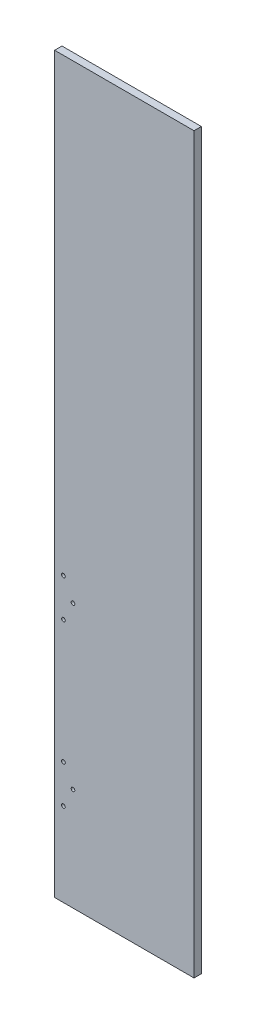
SolidWorks part; units mm, degrees
ref_plane "Front Plane" through (0, 0, 0) normal (0, 0, 1) x (1, 0, 0)
ref_plane "Top Plane" through (0, 0, 0) normal (0, 1, 0) x (1, 0, 0)
ref_plane "Right Plane" through (0, 0, 0) normal (1, 0, 0) x (0, 0, -1)
sketch "Sketch1" plane through (0, 0, 0) normal (0, 0, 1) x (1, 0, 0)
  line L1 (95, -500) -> (-95, -500)
  line L2 (95, -500) -> (95, 500)
  line L3 (95, 500) -> (-95, 500)
  line L4 (-95, -500) -> (-95, 500)
  line L5 (95, -500) -> (-95, 500) construction
  line L6 (95, 500) -> (-95, -500) construction
  point P0 (0, 0)
  dimension "D1" = 190
  dimension "D2" = 1000
extrude "Boss-Extrude1" add sketch "Sketch1" along normal blind 10
sketch "Sketch2" plane through (0, 0, 10) normal (0, 0, 1) x (1, 0, 0)
  line L0 (-95, -500) -> (95, -500) construction
  line L1 (-95, 500) -> (-95, -500) construction
  circle A0 centre (-83, -386) radius 2.5
  circle A1 centre (-70, -360) radius 2.5
  circle A2 centre (-83, -334) radius 2.5
  circle A3 centre (-83, -166) radius 2.5
  circle A4 centre (-70, -140) radius 2.5
  circle A5 centre (-83, -114) radius 2.5
  dimension "D1" = 114
  dimension "D2" = 12
  dimension "D3" = 140
  dimension "D4" = 25
  dimension "D5" = 166
  dimension "D6" = 12
  dimension "D7" = 12
  dimension "D8" = 360
  dimension "D9" = 334
  dimension "D10" = 25
  dimension "D11" = 12
  dimension "D12" = 386
extrude "Cut-Extrude1" cut sketch "Sketch2" against normal through all
